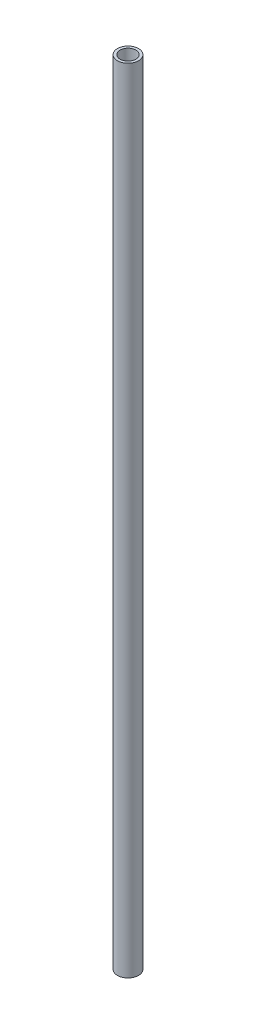
SolidWorks part; units mm, degrees
ref_plane "Front Plane" through (0, 0, 0) normal (0, 0, 1) x (1, 0, 0)
ref_plane "Top Plane" through (0, 0, 0) normal (0, 1, 0) x (1, 0, 0)
ref_plane "Right Plane" through (0, 0, 0) normal (1, 0, 0) x (0, 0, -1)
sketch "Sketch1" plane through (0, 0, 0) normal (0, 1, 0) x (1, 0, 0)
  circle A0 centre (0, 0) radius 1.5
  circle A1 centre (0, 0) radius 2
  dimension "D1" = 3
  dimension "D2" = 4
extrude "Boss-Extrude1" add sketch "Sketch1" along normal blind 150
